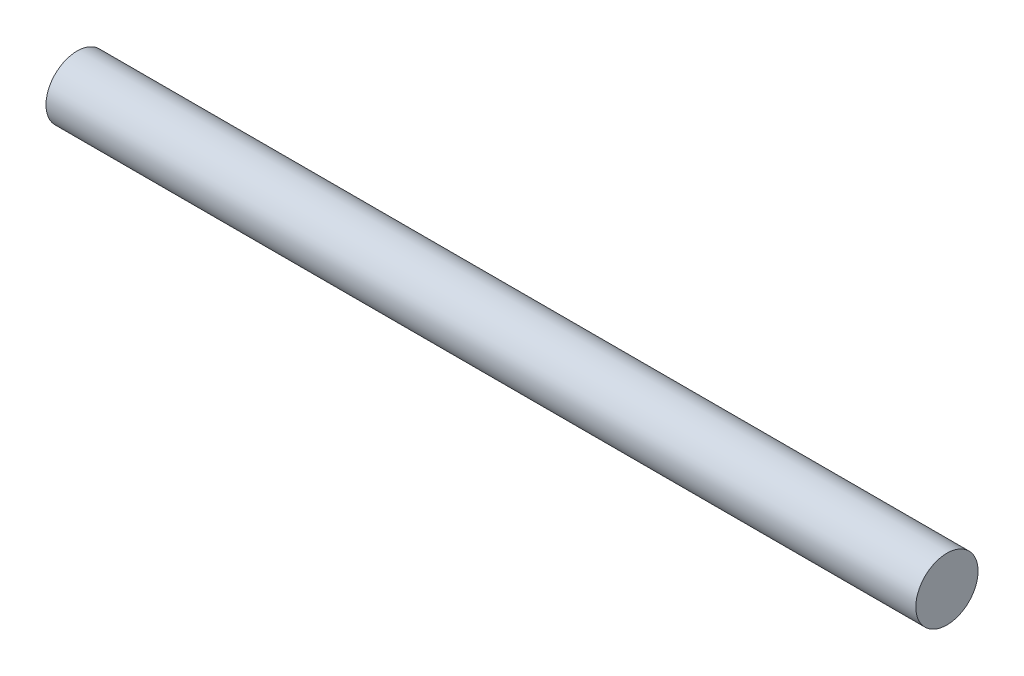
SolidWorks part; units mm, degrees
ref_plane "Ön Düzlem" through (0, 0, 0) normal (0, 0, 1) x (1, 0, 0)
ref_plane "Üst Düzlem" through (0, 0, 0) normal (0, 1, 0) x (1, 0, 0)
ref_plane "Sağ Düzlem" through (0, 0, 0) normal (1, 0, 0) x (0, 0, -1)
sketch "Çizim1" plane through (0, 0, 0) normal (0, 0, 1) x (1, 0, 0)
  line L0 (0, 0) -> (50.3617, 0)
ref_plane "Düzlem1" through (50.3617, 0, 0) normal (1, 0, 0) x (0, 0, -1)
sketch "Çizim2" plane through (50.3617, 0, 0) normal (1, 0, 0) x (0, 0, -1)
  circle A0 centre (0, 0) radius 0.5
  dimension "D1" = 1
sweep "Süpür1" add profiles "Çizim2" path "Çizim1"
sketch "Çizim3" plane through (0, 0, 0) normal (0, 0, 1) x (1, 0, 0)
  line L0 (25.9741, 2.7819) -> (25.9741, -2.7434)
  line L1 (25.9741, -2.7434) -> (51.8398, -2.7434)
  line L2 (51.8398, -2.7434) -> (51.8398, 3.3283)
  line L3 (51.8398, 3.3283) -> (25.9741, 2.7819)
extrude "Kes-Ekstrüzyon1" cut sketch "Çizim3" against normal blind 10
sketch "Çizim4" plane through (0, 0, 0) normal (0, 0, -1) x (-1, 0, 0)
  line L0 (-25.9741, 0.5) -> (-25.9741, -0.5) construction
  line L1 (-26.4336, 0.5) -> (-50.3617, 0.5)
  line L2 (-26.4336, 0.5) -> (-26.4336, -0.5)
  line L3 (-26.4336, -0.5) -> (-50.3617, -0.5)
  line L4 (-50.3617, 0.5) -> (-50.3617, -0.5)
  line L5 (-26.4336, 0.5) -> (-50.3617, -0.5) construction
  line L6 (-26.4336, -0.5) -> (-50.3617, 0.5) construction
  line L7 (-26.4608, 0.5) -> (-25.9741, 0.5)
  line L8 (-26.4608, 0.5) -> (-26.4608, -0.5)
  line L9 (-26.4608, -0.5) -> (-25.9741, -0.5)
  line L10 (-25.9741, 0.5) -> (-25.9741, -0.5)
  line L11 (-26.4608, 0.5) -> (-25.9741, -0.5) construction
  line L12 (-26.4608, -0.5) -> (-25.9741, 0.5) construction
  line L13 (-25.9741, 0.5) -> (-25.9741, -0.5) construction
  point P0 (-38.3977, 0)
  point P6 (-26.2175, 0)
  line M1 (-50.3617, -0.5) -> (-25.9741, -0.5)
  line M2 (-25.9741, -0.5) -> (-25.9741, 0.5)
  line M3 (-25.9741, 0.5) -> (-50.3617, 0.5)
  line M4 (-50.3617, 0.5) -> (-50.3617, -0.5)
extrude "Kes-Ekstrüzyon2" cut sketch "Çizim4" against normal blind 10 contours L8 L1 M4 M1 | L2 M3 M1 M2
sketch "Çizim5" plane through (26.4608, 0, 0) normal (1, 0, 0) x (0, 0, -1)
  line L0 (0, 0.5) -> (0, -0.5)
  arc A0 (0, 0.5) -> (0, -0.5) centre (0, 0) ccw
extrude "Kes-Ekstrüzyon3" cut sketch "Çizim5" against normal blind 0.3
sketch "Çizim6" plane through (0, 0, 0) normal (1, 0, 0) x (0, 0, -1)
  circle A0 centre (0, 0) radius 0.5
extrude "Kes-Ekstrüzyon4" cut sketch "Çizim6" along normal blind 7
sketch "Çizim7" plane through (7, 0, 0) normal (-1, 0, 0) x (0, 0, 1)
  circle A0 centre (0, 0) radius 0.5
extrude "Kes-Ekstrüzyon5" cut sketch "Çizim7" against normal blind 5
